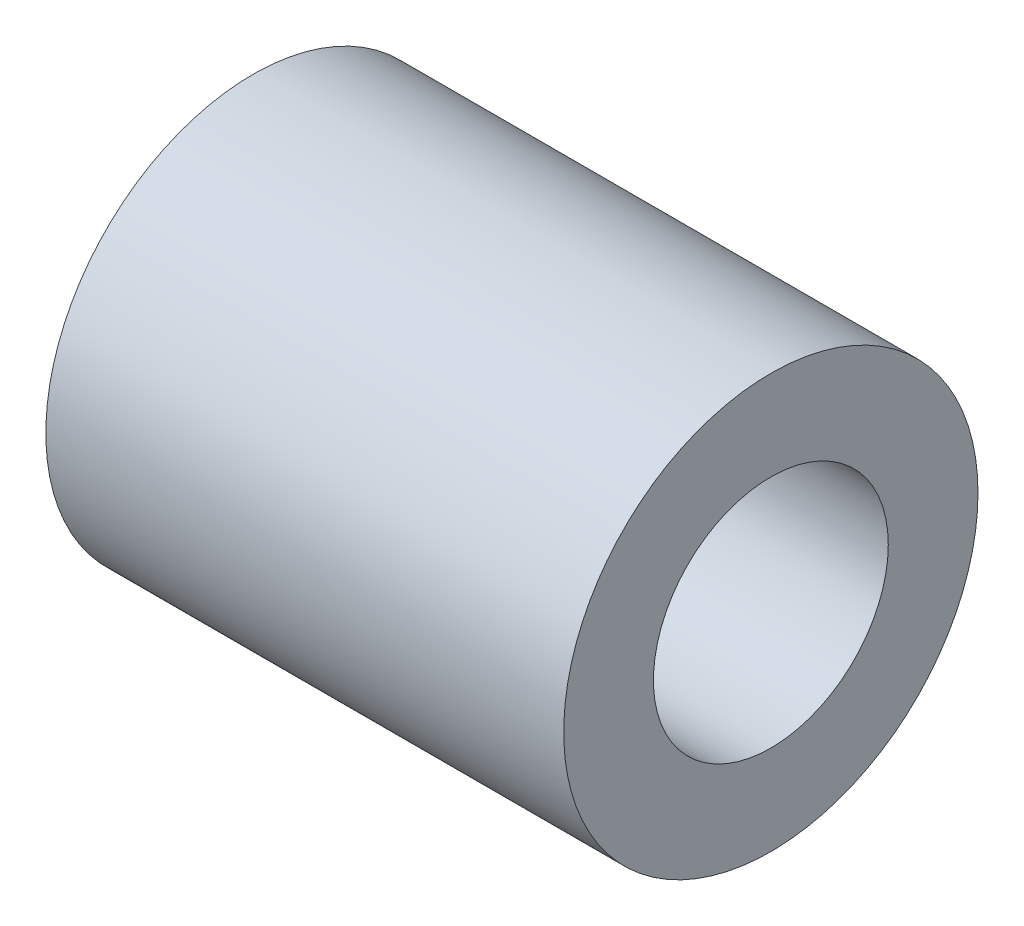
SolidWorks part; units mm, degrees
ref_plane "Front Plane" through (0, 0, 0) normal (0, 0, 1) x (1, 0, 0)
ref_plane "Top Plane" through (0, 0, 0) normal (0, 1, 0) x (1, 0, 0)
ref_plane "Right Plane" through (0, 0, 0) normal (1, 0, 0) x (0, 0, -1)
sketch "Sketch1" plane through (0, 0, 0) normal (1, 0, 0) x (0, 0, -1)
  circle A0 centre (0, 0) radius 1.8
  circle A1 centre (0, 0) radius 3.175
  dimension "D1" = 3.6
  dimension "D2" = 6.35
extrude "Boss-Extrude1" add sketch "Sketch1" along normal blind 7.9375
